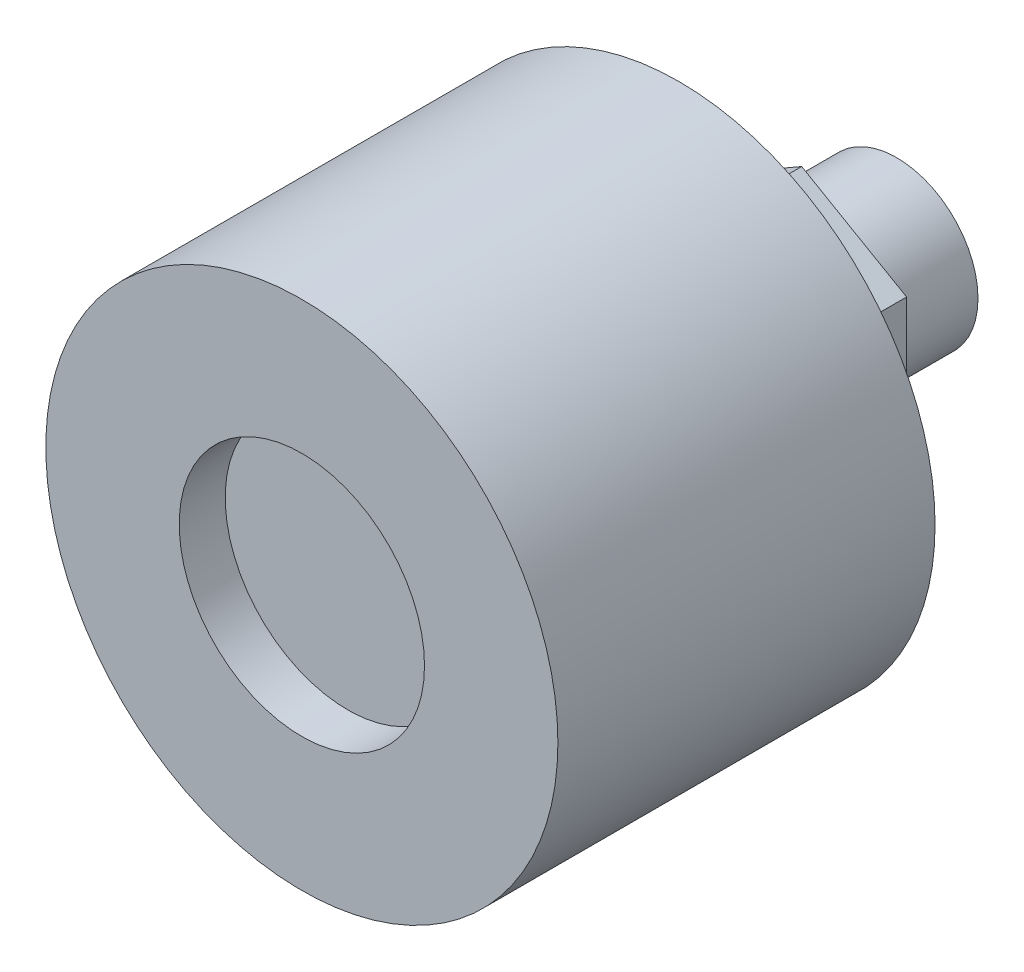
SolidWorks part; units mm, degrees
material "1060 Alloy"
ref_plane "Front Plane" through (0, 0, 0) normal (0, 0, 1) x (1, 0, 0)
ref_plane "Top Plane" through (0, 0, 0) normal (0, 1, 0) x (1, 0, 0)
ref_plane "Right Plane" through (0, 0, 0) normal (1, 0, 0) x (0, 0, -1)
sketch "Sketch3" plane through (0, 0, 0) normal (0, 0, 1) x (1, 0, 0)
  circle A0 centre (0, 0) radius 8.35
  circle A1 centre (0, 0) radius 4
  dimension "D1" = 16.7
extrude "Boss-Extrude1" add sketch "Sketch3" along normal blind 1 and the other way blind 0.5
sketch "Sketch4" plane through (0, 0, -0.5) normal (0, 0, -1) x (-1, 0, 0)
  circle A0 centre (0, 0) radius 8.35
extrude "Boss-Extrude2" add sketch "Sketch4" along normal blind 10.8
sketch "Sketch5" plane through (0, 0, -11.3) normal (0, 0, -1) x (-1, 0, 0)
  line L0 (0, -3.95) -> (0, 3.95) construction
  line L2 (0, 3.95) -> (-3.4208, 1.975)
  line L3 (-3.4208, 1.975) -> (-3.4208, -1.975)
  line L4 (-3.4208, -1.975) -> (0, -3.95)
  line L5 (0, -3.95) -> (3.4208, -1.975)
  line L6 (3.4208, -1.975) -> (3.4208, 1.975)
  line L7 (3.4208, 1.975) -> (0, 3.95)
  circle A1 centre (0, 0) radius 3.4208 construction
  point P6 (0, 0)
  point P9 (0, 3.95)
  point P13 (0, -3.95)
  dimension "D1" = 7.9
extrude "Boss-Extrude4" add sketch "Sketch5" along normal blind 4
sketch "Sketch6" plane through (0, 0, -15.3) normal (0, 0, -1) x (-1, 0, 0)
  circle A0 centre (0, 0) radius 2.65
  dimension "D1" = 5.3
extrude "Boss-Extrude5" add sketch "Sketch6" along normal blind 3.1
sketch "Sketch7" plane through (0, 0, -18.4) normal (0, 0, -1) x (-1, 0, 0)
  circle A0 centre (0, 0) radius 0.2443
extrude "Cut-Extrude1" cut sketch "Sketch7" against normal blind 2
